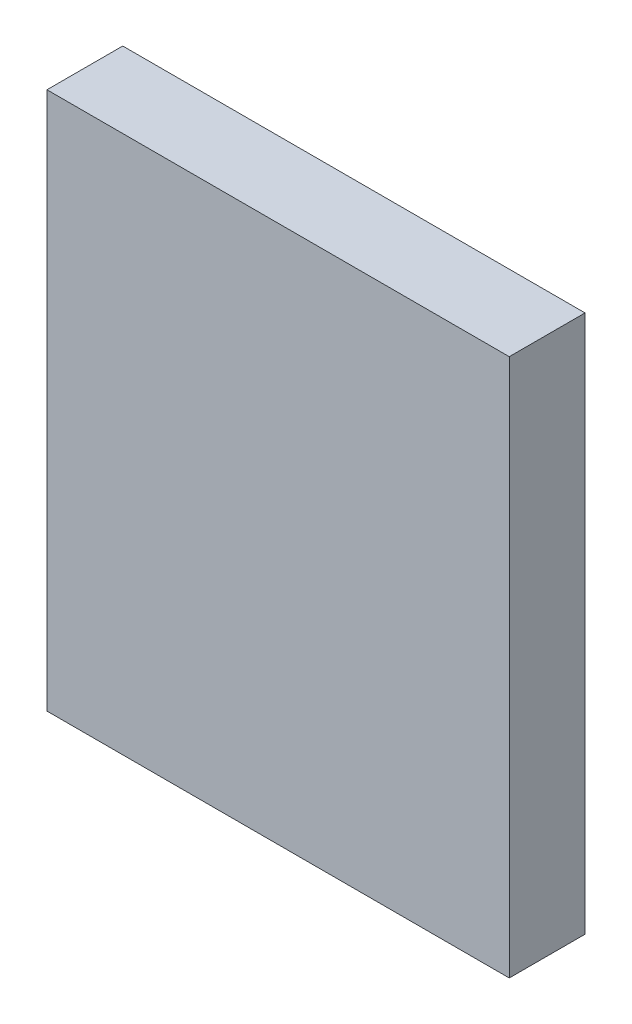
SolidWorks part; units mm, degrees
ref_plane "前视基准面" through (0, 0, 0) normal (0, 0, 1) x (1, 0, 0)
ref_plane "上视基准面" through (0, 0, 0) normal (0, 1, 0) x (1, 0, 0)
ref_plane "右视基准面" through (0, 0, 0) normal (1, 0, 0) x (0, 0, -1)
sketch "草图1" plane through (0, 0, 0) normal (0, 0, 1) x (1, 0, 0)
  line L0 (-3.05, 3.55) -> (-3.05, -3.55)
  line L1 (-3.05, -3.55) -> (3.05, -3.55)
  line L2 (3.05, -3.55) -> (3.05, 3.55)
  line L3 (3.05, 3.55) -> (-3.05, 3.55)
extrude "Component_Outline" add sketch "草图1" along normal blind 1 separate body
sketch3d "3D草图1"
  line L0 (0, 0, 0) -> (1, 0, 0)
  line L1 (0, 0, 0) -> (0, 1, 0)
  line L2 (0, 0, 0) -> (0, 0, 1)
  point P0 (0, 0, 0)
